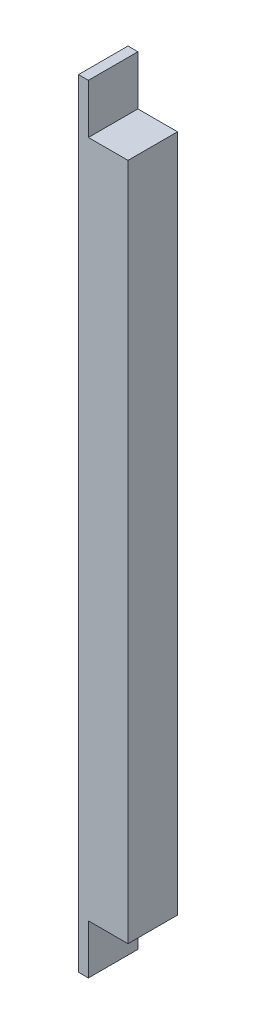
SolidWorks part; units mm, degrees
ref_plane "Plan de face" through (0, 0, 0) normal (0, 0, 1) x (1, 0, 0)
ref_plane "Plan de dessus" through (0, 0, 0) normal (0, 1, 0) x (1, 0, 0)
ref_plane "Plan de droite" through (0, 0, 0) normal (1, 0, 0) x (0, 0, -1)
sketch "Esquisse1" plane through (0, 0, 0) normal (0, 1, 0) x (1, 0, 0)
  line L1 (0, 0) -> (10, 0)
  line L2 (0, 0) -> (0, 10)
  line L3 (0, 10) -> (10, 10)
  line L4 (10, 0) -> (10, 10)
  dimension "D1" = 10
  dimension "D2" = 10
extrude "Boss.-Extru.1" add sketch "Esquisse1" along normal blind 157
sketch "Esquisse2" plane through (10, 0, 0) normal (1, 0, 0) x (0, 0, -1)
  line L0 (0, 157) -> (0, 0) construction
  line L1 (10, 157) -> (0, 157)
  line L2 (10, 157) -> (10, 147)
  line L3 (10, 147) -> (0, 147)
  line L4 (0, 157) -> (0, 147)
  line L5 (10, 78.5) -> (-11.2087, 78.5) construction
  line L6 (10, 157) -> (10, 0) construction
  line L7 (0, 0) -> (0, 10)
  line L8 (10, 10) -> (0, 10)
  line L9 (10, 0) -> (10, 10)
  line L10 (10, 0) -> (0, 0)
  dimension "D1" = 10
extrude "Enlèv. mat.-Extru.1" cut sketch "Esquisse2" against normal blind 8
